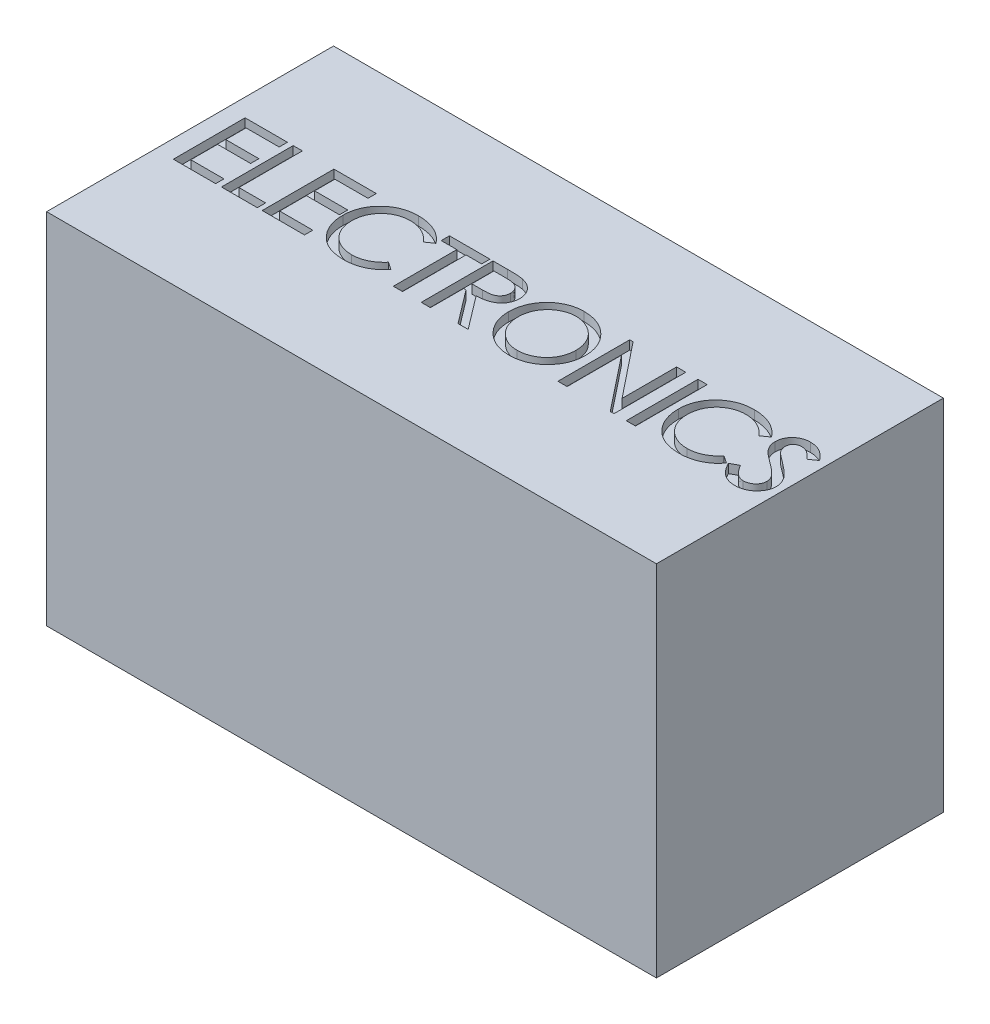
SolidWorks part; units mm, degrees
ref_plane "Front Plane" through (0, 0, 0) normal (0, 0, 1) x (1, 0, 0)
ref_plane "Top Plane" through (0, 0, 0) normal (0, 1, 0) x (1, 0, 0)
ref_plane "Right Plane" through (0, 0, 0) normal (1, 0, 0) x (0, 0, -1)
sketch "Sketch1" plane through (0, 0, 0) normal (0, 0, 1) x (1, 0, 0)
  line L1 (-107.95, 63.5) -> (107.95, 63.5)
  line L2 (-107.95, 63.5) -> (-107.95, -63.5)
  line L3 (-107.95, -63.5) -> (107.95, -63.5)
  line L4 (107.95, 63.5) -> (107.95, -63.5)
  line L5 (-107.95, 63.5) -> (107.95, -63.5) construction
  line L6 (-107.95, -63.5) -> (107.95, 63.5) construction
  point P0 (0, 0)
  dimension "D1" = 127
  dimension "D2" = 215.9
extrude "Boss-Extrude1" add sketch "Sketch1" along normal blind 101.6
sketch "Sketch2" plane through (0, 63.5, 0) normal (0, 1, 0) x (1, 0, 0)
  text T0 "ELECTRONICS" font "Century Gothic" height 25.4
extrude "Cut-Extrude1" cut sketch "Sketch2" against normal blind 3.175
